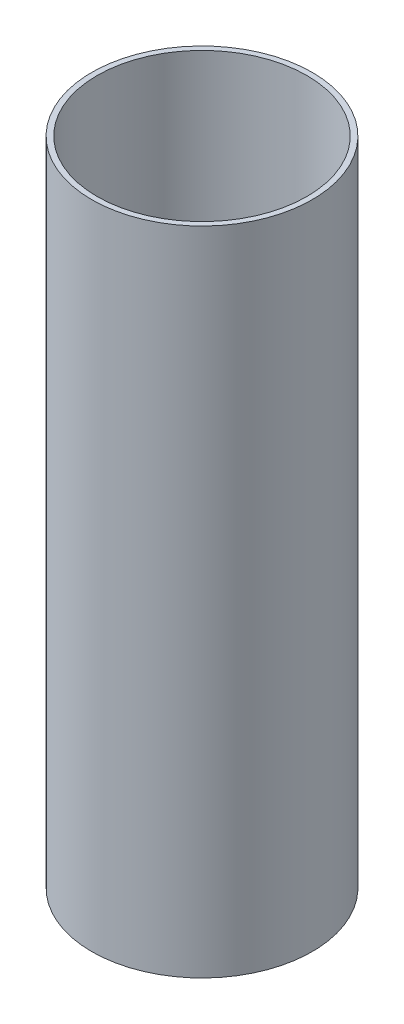
SolidWorks part; units mm, degrees
ref_plane "Front Plane" through (0, 0, 0) normal (0, 0, 1) x (1, 0, 0)
ref_plane "Top Plane" through (0, 0, 0) normal (0, 1, 0) x (1, 0, 0)
ref_plane "Right Plane" through (0, 0, 0) normal (1, 0, 0) x (0, 0, -1)
sketch "Sketch1" plane through (0, 0, 0) normal (0, 1, 0) x (1, 0, 0)
  circle A0 centre (0, 0) radius 25.4
  circle A1 centre (0, 0) radius 24.1554
  dimension "D1" = 1.2446
  dimension "D2" = 50.8
extrude "Boss-Extrude1" add sketch "Sketch1" along normal blind 150
